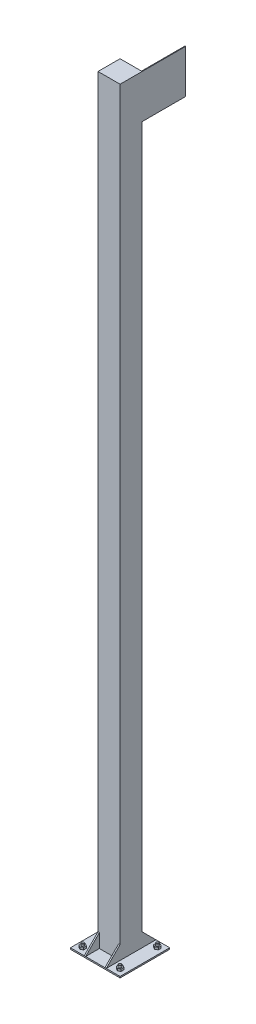
SolidWorks part; units mm, degrees
ref_plane "Alzado" through (0, 0, 0) normal (0, 0, 1) x (1, 0, 0)
ref_plane "Planta" through (0, 0, 0) normal (0, 1, 0) x (1, 0, 0)
ref_plane "Vista lateral" through (0, 0, 0) normal (1, 0, 0) x (0, 0, -1)
sketch "Croquis1" plane through (0, 0, 0) normal (0, 1, 0) x (1, 0, 0)
  line L0 (3, 98.6) -> (98.6, 98.6)
  line L1 (0, 0) -> (101.6, 0)
  line L2 (0, 0) -> (0, 101.6)
  line L3 (0, 101.6) -> (101.6, 101.6)
  line L4 (101.6, 0) -> (101.6, 101.6)
  line L5 (98.6, 3) -> (98.6, 98.6)
  line L6 (3, 3) -> (98.6, 3)
  line L7 (3, 3) -> (3, 98.6)
  dimension "D1" = 101.6
  dimension "D2" = 101.6
  dimension "D3" = 3
extrude "Saliente-Extruir1" add sketch "Croquis1" along normal blind 3500
sketch "Croquis2" plane through (0, 0, 0) normal (0, -1, 0) x (1, 0, 0)
  line L0 (50.8, 0) -> (50.8, -101.6) construction
  line L1 (0, 0) -> (101.6, 0) construction
  line L2 (101.6, -101.6) -> (0, -101.6) construction
  line L4 (165.1, -165.1) -> (-63.5, -165.1)
  line L5 (165.1, -165.1) -> (165.1, 63.5)
  line L6 (165.1, 63.5) -> (-63.5, 63.5)
  line L7 (-63.5, -165.1) -> (-63.5, 63.5)
  line L8 (165.1, -165.1) -> (-63.5, 63.5) construction
  line L9 (165.1, 63.5) -> (-63.5, -165.1) construction
  point P6 (50.8, -50.8)
  dimension "D1" = 228.6
  dimension "D2" = 228.6
extrude "Saliente-Extruir2" add sketch "Croquis2" against normal blind 6.35
sketch "Croquis5" plane through (0, 0, 0) normal (-1, 0, 0) x (0, 0, 1)
  line L0 (-101.6, 6.35) -> (-165.1, 6.35)
  line L1 (-165.1, 6.35) -> (-101.6, 69.85)
  line L2 (-101.6, 3500) -> (-101.6, 6.35) construction
  line L3 (-101.6, 69.85) -> (-101.6, 6.35)
  line L4 (63.5, 6.35) -> (0, 6.35)
  line L5 (0, 6.35) -> (0, 69.85)
  line L6 (0, 3500) -> (0, 6.35) construction
  line L7 (0, 69.85) -> (63.5, 6.35)
  dimension "D1" = 45
extrude "Saliente-Extruir5" add sketch "Croquis5" against normal blind 6.35
sketch "Croquis6" plane through (101.6, 0, 0) normal (1, 0, 0) x (0, 0, -1)
  line L0 (0, 69.85) -> (-63.5, 6.35)
  line L1 (-63.5, 6.35) -> (0, 6.35)
  line L2 (0, 6.35) -> (0, 69.85)
  line L3 (101.6, 69.85) -> (165.1, 6.35)
  line L4 (165.1, 6.35) -> (101.6, 6.35)
  line L5 (101.6, 6.35) -> (101.6, 69.85)
extrude "Saliente-Extruir6" add sketch "Croquis6" against normal blind 6.35
sketch "Croquis7" plane through (0, 6.35, 0) normal (0, 1, 0) x (1, 0, 0)
  line L0 (165.1, 165.1) -> (101.6, 101.6) construction
  line L1 (165.1, 50.8) -> (-63.5, 50.8) construction
  line L2 (165.1, 165.1) -> (165.1, -63.5) construction
  line L3 (-63.5, -63.5) -> (-63.5, 165.1) construction
  line L4 (50.8, 165.1) -> (50.8, -63.5) construction
  line L5 (6.35, 165.1) -> (95.25, 165.1) construction
  line L6 (95.25, -63.5) -> (6.35, -63.5) construction
  circle A0 centre (136.8157, 136.8157) radius 6.35
  circle A1 centre (136.8157, -35.2157) radius 6.35
  circle A2 centre (-35.2157, -35.2157) radius 6.35
  circle A3 centre (-35.2157, 136.8157) radius 6.35
  dimension "D1" = 40
  dimension "D2" = 12.7
extrude "Saliente-Extruir7" add sketch "Croquis7" along normal blind 20
sketch "Croquis8" plane through (0, 6.35, 0) normal (0, 1, 0) x (1, 0, 0)
  line L0 (165.1, 50.8) -> (-63.5, 50.8) construction
  line L1 (136.8157, 124.1959) -> (147.7448, 130.5058)
  line L2 (147.7448, 130.5058) -> (147.7448, 143.1256)
  line L3 (147.7448, 143.1256) -> (136.8157, 149.4356)
  line L4 (136.8157, 149.4356) -> (125.8866, 143.1256)
  line L5 (125.8866, 143.1256) -> (125.8866, 130.5058)
  line L6 (125.8866, 130.5058) -> (136.8157, 124.1959)
  line L7 (165.1, 165.1) -> (165.1, -63.5) construction
  line L8 (-63.5, -63.5) -> (-63.5, 165.1) construction
  line L9 (125.8866, -28.9058) -> (136.8157, -22.5959)
  line L10 (125.8866, -41.5256) -> (125.8866, -28.9058)
  line L11 (136.8157, -47.8356) -> (125.8866, -41.5256)
  line L12 (147.7448, -41.5256) -> (136.8157, -47.8356)
  line L13 (147.7448, -28.9058) -> (147.7448, -41.5256)
  line L14 (136.8157, -22.5959) -> (147.7448, -28.9058)
  line L15 (50.8, 165.1) -> (50.8, -63.5) construction
  line L16 (6.35, 165.1) -> (95.25, 165.1) construction
  line L17 (95.25, -63.5) -> (6.35, -63.5) construction
  line L18 (-35.2157, -22.5959) -> (-46.1448, -28.9058)
  line L19 (-46.1448, -28.9058) -> (-46.1448, -41.5256)
  line L20 (-46.1448, -41.5256) -> (-35.2157, -47.8356)
  line L21 (-35.2157, -47.8356) -> (-24.2866, -41.5256)
  line L22 (-24.2866, -41.5256) -> (-24.2866, -28.9058)
  line L23 (-24.2866, -28.9058) -> (-35.2157, -22.5959)
  line L24 (-24.2866, 130.5058) -> (-35.2157, 124.1959)
  line L25 (-24.2866, 143.1256) -> (-24.2866, 130.5058)
  line L26 (-35.2157, 149.4356) -> (-24.2866, 143.1256)
  line L27 (-46.1448, 143.1256) -> (-35.2157, 149.4356)
  line L28 (-46.1448, 130.5058) -> (-46.1448, 143.1256)
  line L29 (-35.2157, 124.1959) -> (-46.1448, 130.5058)
  circle A0 centre (136.8157, 136.8157) radius 10.9291 construction
  circle A1 centre (136.8157, -35.2157) radius 10.9291 construction
  circle A2 centre (-35.2157, -35.2157) radius 10.9291 construction
  circle A3 centre (-35.2157, 136.8157) radius 10.9291 construction
  circle A4 centre (136.8157, 136.8157) radius 6.35
  circle A5 centre (136.8157, -35.2157) radius 6.35
  circle A6 centre (-35.2157, -35.2157) radius 6.35
  circle A7 centre (-35.2157, 136.8157) radius 6.35
extrude "Saliente-Extruir8" add sketch "Croquis8" along normal blind 10
chamfer "Chaflán1" distance 1 angle 45 4 edges at (136.8157, 26.35, 28.8657) (-35.2157, 26.35, 41.5657) (-35.2157, 26.35, -143.1657) (136.8157, 26.35, -130.4657)
sketch "Croquis9" plane through (0, 3500, 0) normal (0, 1, 0) x (1, 0, 0)
  line L1 (3, 3) -> (98.6, 3)
  line L2 (3, 3) -> (3, 98.6)
  line L3 (3, 98.6) -> (98.6, 98.6)
  line L4 (98.6, 3) -> (98.6, 98.6)
extrude "Saliente-Extruir9" add sketch "Croquis9" against normal blind 3
sketch "Croquis10" plane through (101.6, 0, 0) normal (1, 0, 0) x (0, 0, -1)
  line L1 (101.6, 3500) -> (301.6, 3500)
  line L2 (101.6, 3500) -> (101.6, 3300)
  line L3 (101.6, 3300) -> (301.6, 3300)
  line L4 (301.6, 3500) -> (301.6, 3300)
  dimension "D1" = 200
  dimension "D2" = 200
extrude "Saliente-Extruir10" add sketch "Croquis10" against normal blind 3
